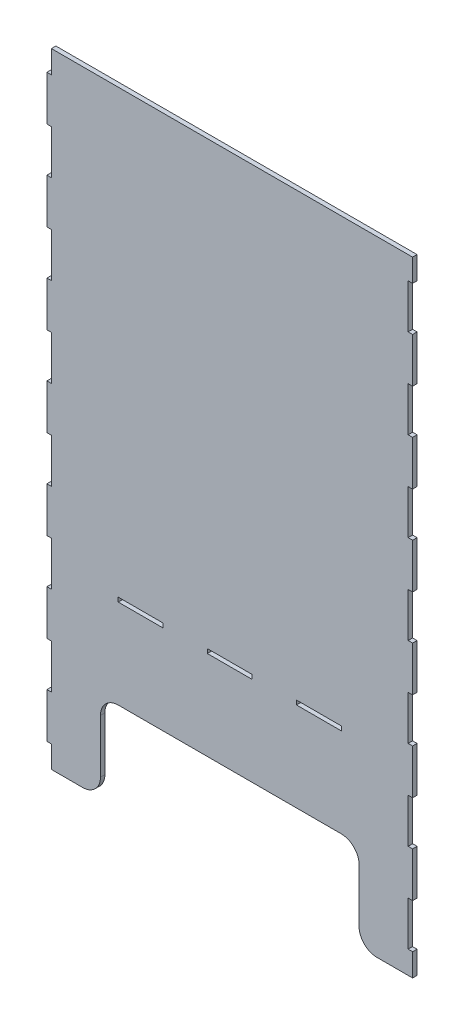
SolidWorks part; units mm, degrees
ref_plane "Ebene vorne" through (0, 0, 0) normal (0, 0, 1) x (1, 0, 0)
ref_plane "Ebene oben" through (0, 0, 0) normal (0, 1, 0) x (1, 0, 0)
ref_plane "Ebene rechts" through (0, 0, 0) normal (1, 0, 0) x (0, 0, -1)
sketch "Skizze1" plane through (0, 0, 0) normal (0, 0, 1) x (1, 0, 0)
  line L0 (0, 0) -> (0, 700)
  line L1 (0, 700) -> (410, 700)
  line L2 (410, 700) -> (410, 0)
  line L3 (410, 0) -> (370, 0)
  line L4 (0, 100) -> (410, 100) construction
  line L5 (60, 20) -> (60, 80)
  line L6 (350, 20) -> (350, 80)
  line L7 (330, 100) -> (80, 100)
  line L8 (40, 0) -> (0, 0)
  arc A0 (80, 100) -> (60, 80) centre (80, 80) ccw
  arc A1 (330, 100) -> (350, 80) centre (330, 80) cw
  arc A2 (40, 0) -> (60, 20) centre (40, 20) ccw
  arc A3 (370, 0) -> (350, 20) centre (370, 20) cw
  point P13 (60, 100)
  point P16 (350, 100)
  point P19 (60, 0)
  point P22 (350, 0)
  dimension "D4" = 20
  dimension "D5" = 20
  dimension "D8" = 20
  dimension "D9" = 20
  dimension "D1" = 700
  dimension "D2" = 410
  dimension "D3" = 100
  dimension "D6" = 60
  dimension "D7" = 60
extrude "Aufsatz-Linear austragen1" add sketch "Skizze1" along normal blind 5 contours L0 L1 L2 L3 A3 L6 A1 L7 A0 L5 A2 L8
sketch "Skizze2" plane through (0, 0, 5) normal (0, 0, 1) x (1, 0, 0)
  line L0 (0, 0) -> (0, 700) construction
  line L1 (79.95, 204.8) -> (130.25, 204.8)
  line L2 (79.95, 204.8) -> (79.95, 200)
  line L3 (79.95, 200) -> (130.25, 200)
  line L4 (130.25, 204.8) -> (130.25, 200)
  point P8 (13.0057, 298.352)
  dimension "D1" = 50.3
  dimension "D2" = 4.8
  dimension "D3" = 79.95
  dimension "D4" = 200
extrude "Schnitt-Linear austragen1" cut sketch "Skizze2" against normal blind 5
pattern_linear "Lineares Muster1" count 3 spacing 99.9 along (1, 0, 0) of "Schnitt-Linear austragen1"
sketch "Skizze3" plane through (0, 0, 5) normal (0, 0, 1) x (1, 0, 0)
  line L0 (0, 700) -> (410, 700) construction
  line L1 (-87.9124, 674.5) -> (5, 674.5)
  line L2 (-87.9124, 674.5) -> (-87.9124, 724.1)
  line L3 (-87.9124, 724.1) -> (5, 724.1)
  line L4 (5, 674.5) -> (5, 724.1)
  dimension "D1" = 49.6
  dimension "D2" = 5
  dimension "D3" = 24.1
extrude "Schnitt-Linear austragen2" cut sketch "Skizze3" against normal blind 5
pattern_linear "Lineares Muster2" count 8 spacing 99.9 along (0, -1, 0) of "Schnitt-Linear austragen2"
ref_plane "Ebene1" through (205, 0, 0) normal (1, 0, 0) x (0, 0, -1)
mirror "Spiegeln2" [suppressed] about plane through (205, 0, 0) normal (1, 0, 0)
sketch "Skizze5" [suppressed] plane through (0, 0, 5) normal (0, 0, 1) x (1, 0, 0)
  line L1 (5, 50.3) -> (-32.3107, 50.3)
  line L2 (5, 50.3) -> (5, -36.4204)
  line L3 (5, -36.4204) -> (-32.3107, -36.4204)
  line L4 (-32.3107, 50.3) -> (-32.3107, -36.4204)
extrude "Schnitt-Linear austragen3" [suppressed] cut sketch "Skizze5" against normal blind 5
sketch "Skizze4" plane through (0, 0, 5) normal (0, 0, 1) x (1, 0, 0)
  line L1 (405, 674.5) -> (491.468, 674.5)
  line L2 (405, 674.5) -> (405, 624.9)
  line L3 (405, 624.9) -> (491.468, 624.9)
  line L4 (491.468, 674.5) -> (491.468, 624.9)
  line L5 (410, 700) -> (410, 0) construction
  dimension "D1" = 49.6
  dimension "D2" = 5
  dimension "D3" = 25.5
extrude "Schnitt-Linear austragen4" cut sketch "Skizze4" against normal blind 5
pattern_linear "Lineares Muster3" count 7 spacing 99.9 along (0, -1, 0) of "Schnitt-Linear austragen4"
sketch "Skizze6" [suppressed] plane through (0, 0, 5) normal (0, 0, 1) x (1, 0, 0)
  line L14 (130.25, -5) -> (130.25, 0)
  line L15 (130.25, 0) -> (79.95, 0)
  line L16 (79.95, 0) -> (79.95, -5)
  line L17 (79.95, -5) -> (130.25, -5)
  line L18 (230.15, -5) -> (230.15, 0)
  line L19 (230.15, 0) -> (179.85, 0)
  line L20 (179.85, 0) -> (179.85, -5)
  line L21 (179.85, -5) -> (230.15, -5)
  line L22 (330.05, -5) -> (330.05, 0)
  line L23 (330.05, 0) -> (279.75, 0)
  line L24 (279.75, 0) -> (279.75, -5)
  line L25 (279.75, -5) -> (330.05, -5)
  line L26 (405, 0) -> (405, -5)
  line L27 (5, 0) -> (5, -5)
  point P16 (0, 0)
sketch "Skizze8" [suppressed] plane through (0, 0, 5) normal (0, 0, 1) x (1, 0, 0)
  line L0 (336.9108, 311.7971) -> (336.9108, 326.3757)
  line L1 (328.6083, 313.8519) -> (328.6083, 327.2541)
  line L2 (328.6083, 333.6697) -> (328.6083, 343.167)
  line L3 (336.9108, 332.9761) -> (336.9108, 342.6373)
  line L4 (327.3926, 291.1393) -> (324.9309, 261.8997)
  line L5 (336.9108, 292.9614) -> (336.9108, 262.1213)
  line L6 (361.3498, 305.4845) -> (370.8351, 305.9572)
  line L7 (340.5076, 297.1544) -> (354.5447, 297.1544)
  line L8 (319.162, 305.9572) -> (306.9363, 311.3902)
  line L9 (319.162, 298.8014) -> (305.6301, 298.0451)
  line L10 (301.0772, 313.9939) -> (292.4018, 317.8492)
  line L11 (299.1984, 297.6857) -> (289.6925, 297.1544)
  line L12 (361.0653, 297.1544) -> (370.6564, 297.1544)
  line L13 (341.558, 304.4982) -> (354.9423, 305.1652)
  line L14 (354.9423, 305.1652) -> (354.4332, 305.5514)
  line L15 (88.2286, 278.6972) -> (88.2286, 273.2138)
  line L16 (102.4933, 343.167) -> (102.4933, 259.9015) construction
  line L17 (116.7579, 273.2138) -> (116.7579, 278.6972)
  line L18 (116.7579, 288.6972) -> (116.7579, 273.2138)
  line L19 (77.4933, 288.6972) -> (78.2286, 288.6972)
  line L20 (126.7579, 288.6972) -> (127.4933, 288.6972)
  line L21 (119.7579, 273.2138) -> (119.7579, 278.6972)
  line L22 (126.7579, 285.6972) -> (127.4933, 285.6972)
  line L23 (77.4933, 285.6972) -> (78.2286, 285.6972)
  line L24 (85.2286, 278.6972) -> (85.2286, 273.2138)
  line L25 (126.7579, 273.2138) -> (126.7579, 278.6972)
  line L26 (126.7579, 282.6972) -> (127.4933, 282.6972)
  line L27 (122.7579, 273.2138) -> (122.7579, 278.6972)
  line L28 (82.2286, 278.6972) -> (82.2286, 273.2138)
  line L29 (77.4933, 282.6972) -> (78.2286, 282.6972)
  line L30 (126.7579, 278.6972) -> (127.4933, 278.6972)
  line L31 (102.4933, 290.7717) -> (102.4933, 229.2493) construction
  line L32 (102.4933, 229.2493) -> (102.4933, 290.7717)
  line L33 (77.4933, 278.6972) -> (78.2286, 278.6972)
  line L34 (78.2286, 278.6972) -> (78.2286, 273.2138)
  line L36 (129.7579, 273.2138) -> (129.7579, 275.8402)
  line L37 (129.7579, 275.8402) -> (129.7579, 275.8402)
  line L38 (75.2286, 275.8402) -> (75.2286, 275.8402)
  line L39 (75.2286, 275.8402) -> (75.2286, 273.2138)
  arc A0 (328.6083, 343.167) -> (292.4018, 317.8492) centre (330.1744, 302.3793) ccw
  arc A1 (328.6083, 333.6697) -> (301.0772, 313.9939) centre (330.1744, 302.3793) ccw
  arc A2 (328.6083, 327.2541) -> (306.9363, 311.3902) centre (330.1744, 302.3793) ccw
  arc A3 (328.6083, 313.8519) -> (319.162, 305.9572) centre (330.1744, 302.3793) ccw
  arc A4 (319.162, 298.8014) -> (340.5076, 297.1544) centre (330.1744, 302.3793) ccw
  arc A5 (305.6301, 298.0451) -> (354.5447, 297.1544) centre (330.1744, 302.3793) ccw
  arc A6 (299.1984, 297.6857) -> (361.0653, 297.1544) centre (330.1744, 302.3793) ccw
  arc A7 (289.6925, 297.1544) -> (370.6564, 297.1544) centre (330.1744, 302.3793) ccw
  arc A8 (341.558, 304.4982) -> (336.9108, 311.7971) centre (330.1744, 302.3793) ccw
  arc A9 (354.9423, 305.1652) -> (336.9108, 326.3757) centre (330.1744, 302.3793) ccw
  arc A10 (361.3498, 305.4845) -> (336.9108, 332.9761) centre (330.1744, 302.3793) ccw
  arc A11 (370.8351, 305.9572) -> (336.9108, 342.6373) centre (330.1744, 302.3793) ccw
  arc A12 (72.5271, 294.2784) -> (132.4594, 294.2784) centre (102.4933, 290.7717) cw
  arc A13 (132.4594, 294.2784) -> (127.4933, 288.6972) centre (127.4933, 293.6972) cw
  arc A14 (72.5271, 294.2784) -> (77.4933, 288.6972) centre (77.4933, 293.6972) ccw
  arc A15 (78.2286, 288.6972) -> (88.2286, 278.6972) centre (78.2286, 278.6972) cw
  arc A16 (126.7579, 288.6972) -> (116.7579, 278.6972) centre (126.7579, 278.6972) ccw
  arc A17 (88.2286, 273.2138) -> (116.7579, 273.2138) centre (102.4933, 273.2138) ccw
  arc A18 (126.7579, 285.6972) -> (119.7579, 278.6972) centre (126.7579, 278.6972) ccw
  arc A19 (135.439, 294.627) -> (127.4933, 285.6972) centre (127.4933, 293.6972) cw
  arc A20 (69.5475, 294.627) -> (135.439, 294.627) centre (102.4933, 290.7717) cw
  arc A21 (69.5475, 294.627) -> (77.4933, 285.6972) centre (77.4933, 293.6972) ccw
  arc A22 (78.2286, 285.6972) -> (85.2286, 278.6972) centre (78.2286, 278.6972) cw
  arc A23 (85.2286, 273.2138) -> (119.7579, 273.2138) centre (102.4933, 273.2138) ccw
  arc A24 (66.5678, 294.9757) -> (138.4187, 294.9757) centre (102.4933, 290.7717) cw
  arc A25 (138.4187, 294.9757) -> (127.4933, 282.6972) centre (127.4933, 293.6972) cw
  arc A26 (126.7579, 282.6972) -> (122.7579, 278.6972) centre (126.7579, 278.6972) ccw
  arc A27 (82.2286, 273.2138) -> (122.7579, 273.2138) centre (102.4933, 273.2138) ccw
  arc A28 (78.2286, 282.6972) -> (82.2286, 278.6972) centre (78.2286, 278.6972) cw
  arc A29 (66.5678, 294.9757) -> (77.4933, 282.6972) centre (77.4933, 293.6972) ccw
  arc A30 (126.7579, 278.6972) -> (126.7579, 278.6972) centre (126.7579, 278.6972) ccw
  arc A31 (142.3916, 295.4406) -> (127.4933, 278.6972) centre (127.4933, 293.6972) cw
  arc A32 (62.5949, 295.4406) -> (142.3916, 295.4406) centre (102.4933, 290.7717) cw
  arc A33 (62.5949, 295.4406) -> (77.4933, 278.6972) centre (77.4933, 293.6972) ccw
  arc A34 (78.2286, 278.6972) -> (78.2286, 278.6972) centre (78.2286, 278.6972) cw
  arc A35 (78.2286, 273.2138) -> (126.7579, 273.2138) centre (102.4933, 273.2138) ccw
  arc A36 (129.7579, 275.8402) -> (129.7579, 275.8402) centre (129.7579, 275.8402) ccw
  arc A37 (145.3713, 295.7893) -> (129.7579, 275.8402) centre (127.4933, 293.6972) cw
  arc A38 (59.6153, 295.7893) -> (145.3713, 295.7893) centre (102.4933, 290.7717) cw
  arc A39 (59.6153, 295.7893) -> (75.2286, 275.8402) centre (77.4933, 293.6972) ccw
  arc A40 (75.2286, 275.8402) -> (75.2286, 275.8402) centre (75.2286, 275.8402) cw
  arc A41 (75.2286, 273.2138) -> (129.7579, 273.2138) centre (102.4933, 273.2138) ccw
  arc A42 (78.2286, 288.6972) -> (88.2286, 278.6972) centre (78.2286, 278.6972) cw construction
  point P29 (0, 0)
  dimension "D1" = 5
  dimension "D2" = 10
  dimension "D3" = 10
  dimension "D4" = 25
  dimension "D5" = 25
  dimension "D6" = 10
  dimension "D7" = 3
  dimension "D8" = 3
equation "\"D1@Ebene1\"=410/2"
